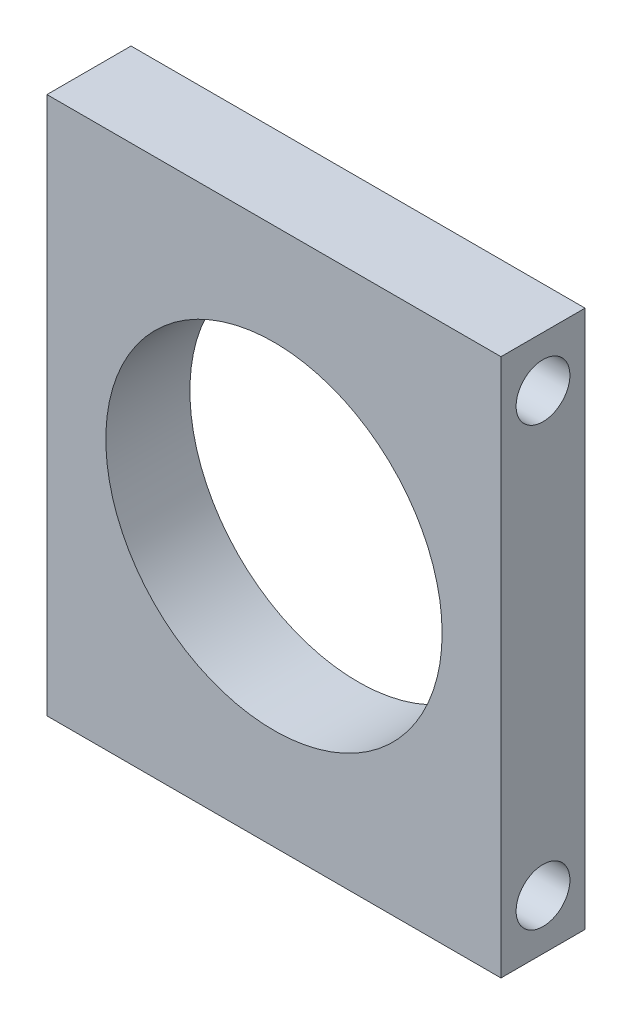
SolidWorks part; units mm, degrees
ref_plane "前视基准面" through (0, 0, 0) normal (0, 0, 1) x (1, 0, 0)
ref_plane "上视基准面" through (0, 0, 0) normal (0, 1, 0) x (1, 0, 0)
ref_plane "右视基准面" through (0, 0, 0) normal (1, 0, 0) x (0, 0, -1)
other "Configuration Table"
sketch "草图2" plane through (0, 0, 0) normal (0, 0, 1) x (1, 0, 0)
  line L1 (0, 0) -> (27, 0)
  line L2 (0, 0) -> (0, -32)
  line L3 (0, -32) -> (27, -32)
  line L4 (27, 0) -> (27, -32)
  dimension "D1" = 27
  dimension "D2" = 32
extrude "凸台-拉伸1" add sketch "草图2" along normal blind 5
sketch "草图3" plane through (0, 0, 5) normal (0, 0, 1) x (1, 0, 0)
  line L0 (0, -16) -> (27, -16) construction
  line L1 (0, 0) -> (0, -32) construction
  line L2 (27, -32) -> (27, 0) construction
  line L3 (13.5, 0) -> (13.5, -32) construction
  line L4 (27, 0) -> (0, 0) construction
  line L5 (0, -32) -> (27, -32) construction
  circle A0 centre (13.5, -16) radius 10
  dimension "D1" = 20
extrude "切除-拉伸1" cut sketch "草图3" against normal blind 64
sketch "草图5" plane through (0, 0, 0) normal (-1, 0, 0) x (0, 0, 1)
  line L0 (2.5, 0) -> (2.5, -32) construction
  line L1 (5, 0) -> (0, 0) construction
  line L2 (5, -32) -> (0, -32) construction
  line L3 (0, -16) -> (5, -16) construction
  line L4 (0, 0) -> (0, -32) construction
  line L5 (5, 0) -> (5, -32) construction
  circle A0 centre (2.5, -3) radius 1.6
  circle A1 centre (2.5, -29) radius 1.6
  dimension "D1" = 26
  dimension "D2" = 3.2
extrude "切除-拉伸2" cut sketch "草图5" against normal blind 64
